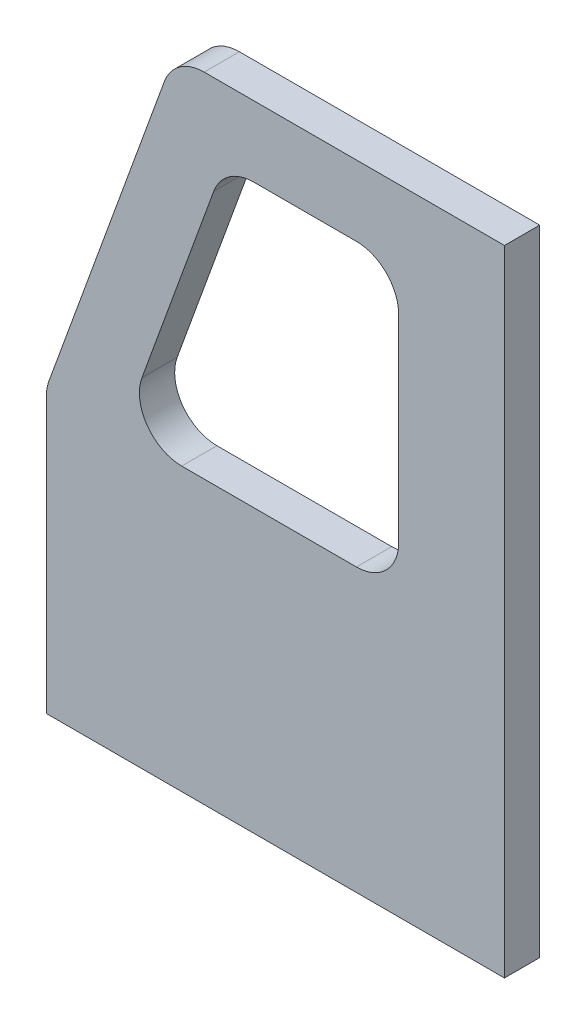
SolidWorks part; units mm, degrees
ref_plane "Plan de face" through (0, 0, 0) normal (0, 0, 1) x (1, 0, 0)
ref_plane "Plan de dessus" through (0, 0, 0) normal (0, 1, 0) x (1, 0, 0)
ref_plane "Plan de droite" through (0, 0, 0) normal (1, 0, 0) x (0, 0, -1)
sketch "Esquisse1" plane through (0, 0, 0) normal (0, 0, 1) x (1, 0, 0)
  line L0 (0, 0) -> (65, 0)
  line L1 (65, 0) -> (65, 90)
  line L2 (65, 90) -> (18.1985, 90)
  line L3 (18.1985, 90) -> (0, 40)
  line L4 (0, 40) -> (0, 0)
  dimension "D1" = 65
  dimension "D2" = 90
  dimension "D3" = 40
  dimension "D4" = 160
extrude "Boss.-Extru.1" add sketch "Esquisse1" along normal blind 5
sketch "Esquisse2" plane through (0, 0, 5) normal (0, 0, 1) x (1, 0, 0)
  line L0 (10.6418, 40) -> (25.2006, 80)
  line L1 (25.2006, 80) -> (50, 80)
  line L2 (50, 80) -> (50, 40)
  line L3 (50, 40) -> (10.6418, 40)
  line L4 (65, 0) -> (65, 90) construction
  line L5 (65, 90) -> (18.1985, 90) construction
  line L6 (18.1985, 90) -> (0, 40) construction
  point P11 (0, 0)
  point P14 (0, 0)
  point P15 (0, 0)
  dimension "D1" = 15
  dimension "D2" = 10
  dimension "D3" = 10
extrude "Enlèv. mat.-Extru.1" cut sketch "Esquisse2" against normal through all both and the other way through all
fillet "Congé1" radius 6 6 edges at (25.2006, 80, 2.5) (50, 80, 2.5) (50, 40, 2.5) (10.6418, 40, 2.5) (18.1985, 90, 2.5) (0, 40, 2.5)
